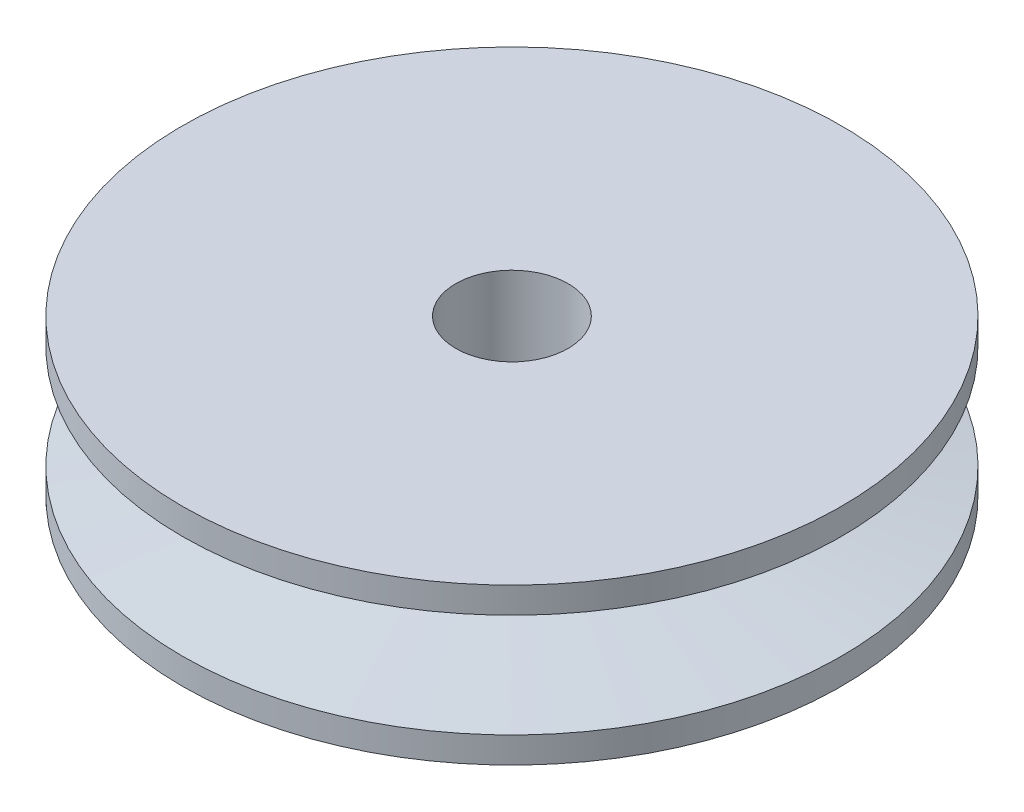
SolidWorks part; units mm, degrees
material "AISI 304"
ref_plane "Front Plane" through (0, 0, 0) normal (0, 0, 1) x (1, 0, 0)
ref_plane "Top Plane" through (0, 0, 0) normal (0, 1, 0) x (1, 0, 0)
ref_plane "Right Plane" through (0, 0, 0) normal (1, 0, 0) x (0, 0, -1)
sketch "Sketch1" plane through (0, 0, 0) normal (1, 0, 0) x (0, 0, -1)
  line L0 (0, 0) -> (41.65, 0)
  line L1 (0, 0) -> (0, -19.7)
  line L2 (0, -19.7) -> (41.65, -19.7)
  line L3 (41.65, -19.7) -> (41.65, -16.4)
  line L4 (41.65, 0) -> (41.65, -3.3)
  line L5 (0, -9.85) -> (45.0465, -9.85) construction
  line L6 (22.5232, -6.5) -> (22.5232, -13.2)
  line L7 (22.5232, -13.2) -> (41.65, -16.4)
  line L8 (22.5232, -6.5) -> (41.65, -3.3)
  dimension "D1" = 41.65
  dimension "D2" = 6.5
  dimension "D3" = 6.5
  dimension "D4" = 3.3
  dimension "D5" = 3.3
revolve "Revolve1" add sketch "Sketch1" angle 360 about L1
sketch "Sketch2" plane through (0, 0, 0) normal (0, 1, 0) x (1, 0, 0)
  circle A0 centre (0, 0) radius 7.1
  dimension "D1" = 14.2
extrude "Cut-Extrude1" cut sketch "Sketch2" against normal through all
